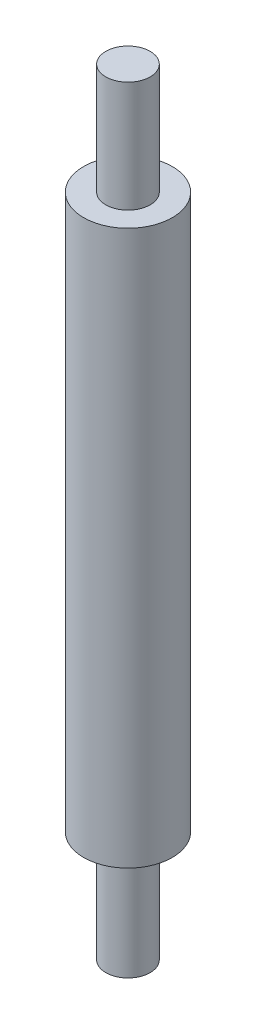
SolidWorks part; units mm, degrees
material "Plain Carbon Steel"
ref_plane "Front Plane" through (0, 0, 0) normal (0, 0, 1) x (1, 0, 0)
ref_plane "Top Plane" through (0, 0, 0) normal (0, 1, 0) x (1, 0, 0)
ref_plane "Right Plane" through (0, 0, 0) normal (1, 0, 0) x (0, 0, -1)
sketch "Sketch1" plane through (0, 0, 0) normal (0, 0, 1) x (1, 0, 0)
  line L0 (0, 35) -> (2, 35)
  line L1 (0, -44.7868) -> (0, 44.7868) construction
  line L2 (2, 35) -> (2, 25)
  line L3 (2, 25) -> (4, 25)
  line L4 (4, 25) -> (4, -25)
  line L5 (4, -25) -> (2, -25)
  line L6 (2, -25) -> (2, -35)
  line L7 (2, -35) -> (0, -35)
  line L8 (0, -35) -> (0, 35)
  line L9 (55, 0) -> (-55, 0) construction
  line L10 (0, 41.4863) -> (0, -40.1571) construction
  point P4 (4, 0)
  dimension "D1" = 10
  dimension "D2" = 10
  dimension "D3" = 4
  dimension "D4" = 2
  dimension "D5" = 50
revolve "Revolve1" add sketch "Sketch1" angle 360 about L10
